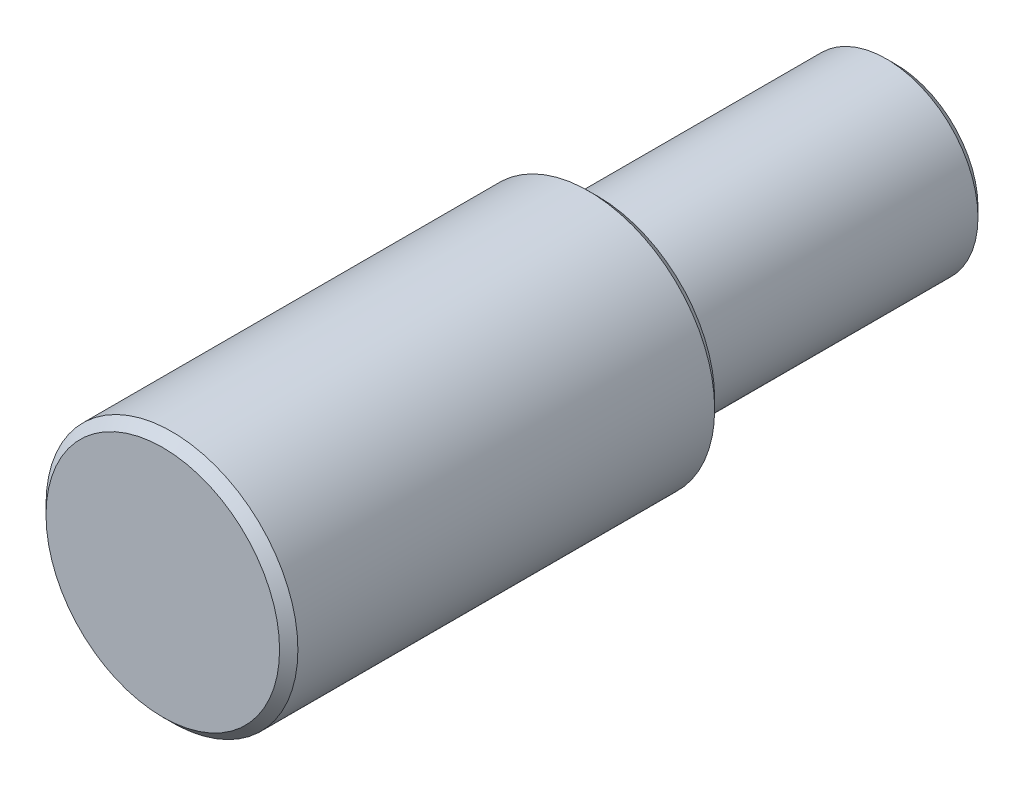
SolidWorks part; units mm, degrees
ref_plane "前视基准面" through (0, 0, 0) normal (0, 0, 1) x (1, 0, 0)
ref_plane "上视基准面" through (0, 0, 0) normal (0, 1, 0) x (1, 0, 0)
ref_plane "右视基准面" through (0, 0, 0) normal (1, 0, 0) x (0, 0, -1)
sketch "草图1" plane through (0, 0, 0) normal (0, 0, 1) x (1, 0, 0)
  circle A0 centre (0, 0) radius 20
  dimension "D1" = 40
extrude "凸台-拉伸1" add sketch "草图1" along normal blind 65
sketch "草图2" plane through (0, 0, 65) normal (0, 0, 1) x (1, 0, 0)
  circle A0 centre (0, 0) radius 27.5
  dimension "D1" = 55
extrude "凸台-拉伸2" add sketch "草图2" along normal blind 95
chamfer "倒角1" distance 2 angle 45 3 edges at (27.5, 0, 160) (27.5, 0, 65) (20, 0, 0)
